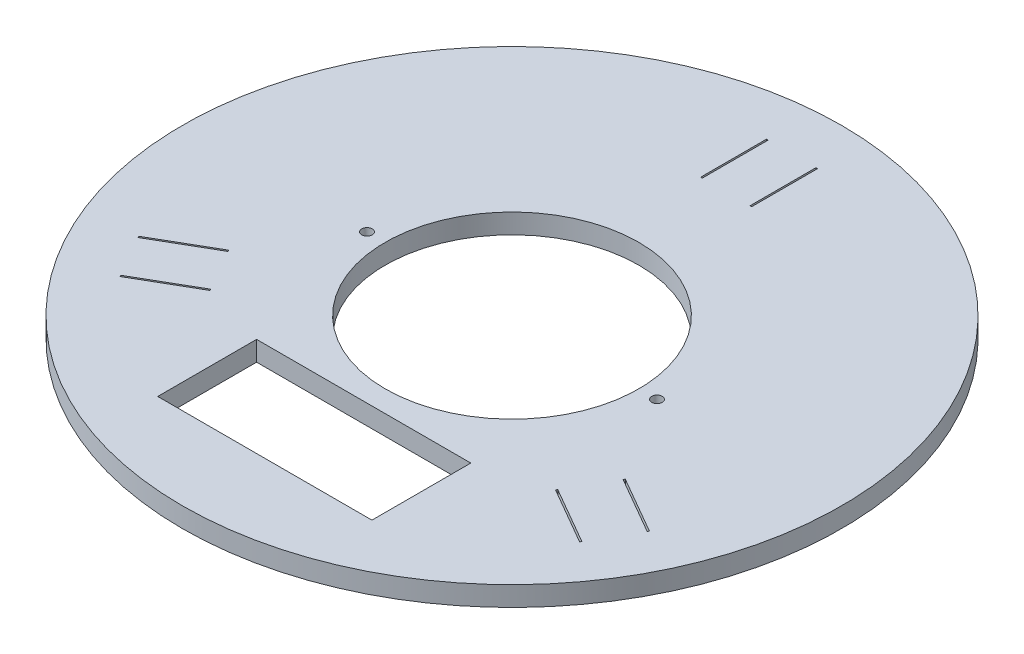
SolidWorks part; units mm, degrees
ref_plane "Front Plane" through (0, 0, 0) normal (0, 0, 1) x (1, 0, 0)
ref_plane "Top Plane" through (0, 0, 0) normal (0, 1, 0) x (1, 0, 0)
ref_plane "Right Plane" through (0, 0, 0) normal (1, 0, 0) x (0, 0, -1)
sketch "Sketch2" plane through (0, 0, 0) normal (0, 1, 0) x (1, 0, 0)
  circle A0 centre (0, 0) radius 100
  dimension "D1" = 200
extrude "Boss-Extrude1" add sketch "Sketch2" along normal blind 6
sketch "Sketch3" plane through (0, 6, 0) normal (0, 1, 0) x (1, 0, 0)
  line L0 (0, 0) -> (0, 100) construction
  line L1 (-7.5, 75) -> (7.5, 75) construction
  line L3 (-7.75, 65) -> (-7.25, 65)
  line L4 (-7.75, 65) -> (-7.75, 85)
  line L5 (-7.75, 85) -> (-7.25, 85)
  line L6 (-7.25, 65) -> (-7.25, 85)
  line L7 (-7.75, 65) -> (-7.25, 85) construction
  line L8 (-7.75, 85) -> (-7.25, 65) construction
  line L9 (7.25, 65) -> (7.75, 65)
  line L10 (7.25, 65) -> (7.25, 85)
  line L11 (7.25, 85) -> (7.75, 85)
  line L12 (7.75, 65) -> (7.75, 85)
  line L13 (7.25, 65) -> (7.75, 85) construction
  line L14 (7.25, 85) -> (7.75, 65) construction
  line L30 (60.1667, -25.7883) -> (77.4872, -35.7883)
  line L31 (60.1667, -25.7883) -> (59.9167, -26.2213)
  line L32 (59.9167, -26.2213) -> (77.2372, -36.2213)
  line L33 (77.4872, -35.7883) -> (77.2372, -36.2213)
  line L34 (52.6667, -38.7787) -> (69.9872, -48.7787)
  line L35 (52.6667, -38.7787) -> (52.4167, -39.2117)
  line L36 (52.4167, -39.2117) -> (69.7372, -49.2117)
  line L37 (69.9872, -48.7787) -> (69.7372, -49.2117)
  line L38 (-52.4167, -39.2117) -> (-69.7372, -49.2117)
  line L39 (-52.4167, -39.2117) -> (-52.6667, -38.7787)
  line L40 (-52.6667, -38.7787) -> (-69.9872, -48.7787)
  line L41 (-69.7372, -49.2117) -> (-69.9872, -48.7787)
  line L42 (-59.9167, -26.2213) -> (-77.2372, -36.2213)
  line L43 (-59.9167, -26.2213) -> (-60.1667, -25.7883)
  line L44 (-60.1667, -25.7883) -> (-77.4872, -35.7883)
  line L45 (-77.2372, -36.2213) -> (-77.4872, -35.7883)
  circle A0 centre (0, 0) radius 100 construction
  point P8 (0, 75)
  point P36 (0, 0)
  point P37 (0, 0)
  dimension "D1" = 15
  dimension "D2" = 20
  dimension "D3" = 0.5
  dimension "D4" = 75
  dimension "D5" = 3
extrude "Cut-Extrude1" cut sketch "Sketch3" against normal through all
sketch "Sketch4" plane through (0, 6, 0) normal (0, 1, 0) x (1, 0, 0)
  circle A0 centre (0, 0) radius 38.5
  dimension "D1" = 77
extrude "Cut-Extrude2" cut sketch "Sketch4" against normal through all
sketch "Sketch5" plane through (0, 6, 0) normal (0, 1, 0) x (1, 0, 0)
  line L0 (0, 0) -> (50000, 0) construction
  line L1 (0, 0) -> (0, 50000) construction
  circle A0 centre (-44, 0) radius 1.6
  circle A1 centre (44, 0) radius 1.6
  dimension "D2" = 3.2
  dimension "D1" = 44
extrude "Cut-Extrude3" cut sketch "Sketch5" against normal through all
sketch "Sketch6" plane through (0, 6, 0) normal (0, 1, 0) x (1, 0, 0)
  line L1 (-32.5, -45) -> (32.5, -45)
  line L2 (-32.5, -45) -> (-32.5, -75)
  line L3 (-32.5, -75) -> (32.5, -75)
  line L4 (32.5, -45) -> (32.5, -75)
  point P4 (0, -45)
  dimension "D1" = 45
  dimension "D2" = 30
  dimension "D3" = 65
extrude "Cut-Extrude4" cut sketch "Sketch6" against normal through all
equation "\"Leg_Spacing\"=15"
equation "\"D1@Sketch3\"=\"Leg_Spacing\""
equation "\"Leaf_Spring_Slot_Width\"=20"
equation "\"D2@Sketch3\"=\"Leaf_Spring_Slot_Width\""
equation "\"Leaf_Spring_Thickness\"=0.5"
equation "\"D3@Sketch3\"=\"Leaf_Spring_Thickness\""
equation "\"Inner_Radius\"=75"
equation "\"D4@Sketch3\"=\"Inner_Radius\""
equation "\"Camera\"=77"
equation "\"D1@Sketch4\"=\"Camera\""
